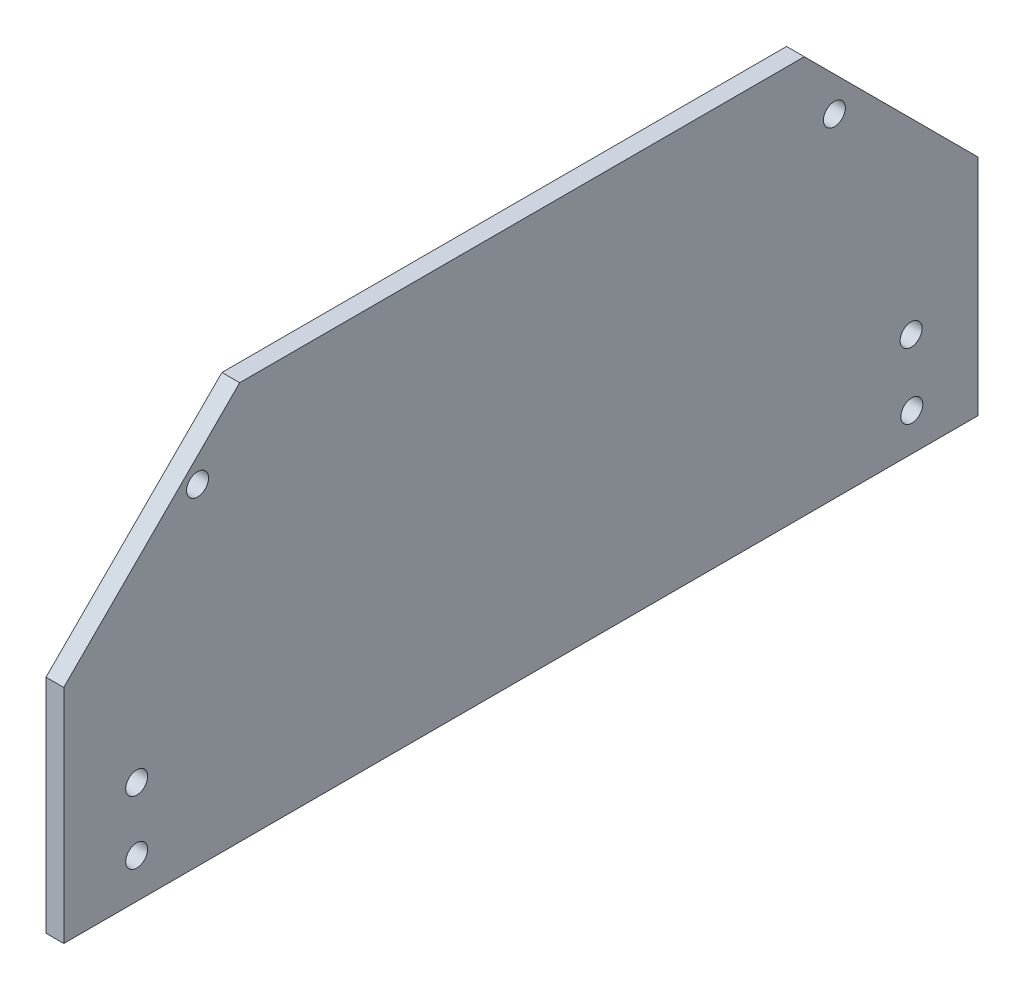
SolidWorks part; units mm, degrees
ref_plane "Front Plane" through (0, 0, 0) normal (0, 0, 1) x (1, 0, 0)
ref_plane "Top Plane" through (0, 0, 0) normal (0, 1, 0) x (1, 0, 0)
ref_plane "Right Plane" through (0, 0, 0) normal (1, 0, 0) x (0, 0, -1)
sketch "Sketch1" plane through (0, 0, 0) normal (1, 0, 0) x (0, 0, -1)
  line L6 (0, 0) -> (0, 37.465)
  line L7 (0, 37.465) -> (29.718, 67.183)
  line L8 (29.718, 67.183) -> (125.095, 67.183)
  line L9 (154.432, 37.846) -> (125.095, 67.183)
  line L10 (154.432, 37.846) -> (154.432, 0)
  line L11 (154.432, 0) -> (0, 0)
  circle A6 centre (12.319, 17.399) radius 1.854
  circle A7 centre (12.319, 6.731) radius 1.854
  circle A8 centre (22.606, 55.88) radius 1.854
  circle A9 centre (130.175, 56.261) radius 1.854
  circle A10 centre (143.256, 6.35) radius 1.854
  circle A11 centre (143.129, 17.526) radius 1.854
  dimension "D15" = 3.708
  dimension "D16" = 3.708
  dimension "D17" = 3.708
  dimension "D20" = 3.708
  dimension "D23" = 3.708
  dimension "D24" = 3.708
  dimension "D1" = 42.0276
  dimension "D2" = 41.4888
  dimension "D3" = 37.846
  dimension "D4" = 95.377
  dimension "D5" = 37.465
  dimension "D7" = 12.319
  dimension "D8" = 12.319
  dimension "D9" = 6.731
  dimension "D10" = 17.399
  dimension "D11" = 6.35
  dimension "D12" = 11.176
  dimension "D13" = 11.303
  dimension "D14" = 17.526
  dimension "D18" = 24.257
  dimension "D19" = 10.922
  dimension "D21" = 11.303
  dimension "D22" = 22.606
extrude "Boss-Extrude1" add sketch "Sketch1" along normal blind 3
